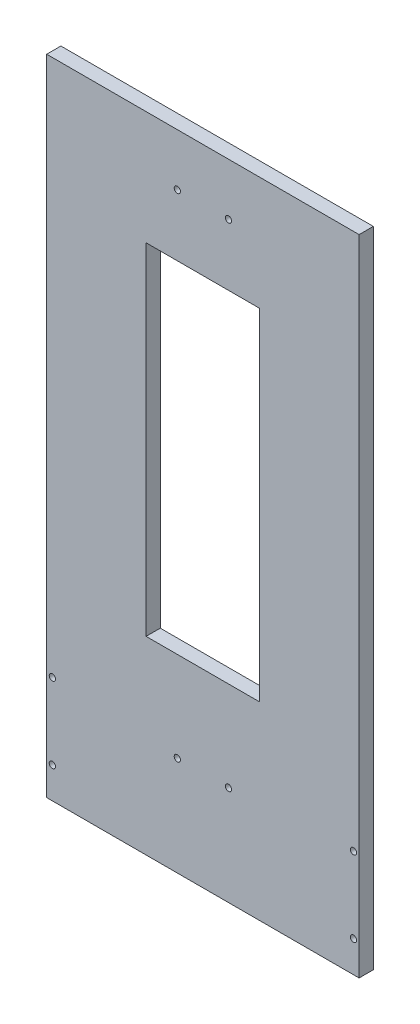
SolidWorks part; units mm, degrees
material "6061 合金"
ref_plane "前视基准面" through (0, 0, 0) normal (0, 0, 1) x (1, 0, 0)
ref_plane "上视基准面" through (0, 0, 0) normal (0, 1, 0) x (1, 0, 0)
ref_plane "右视基准面" through (0, 0, 0) normal (1, 0, 0) x (0, 0, -1)
other "Configuration Table"
sketch "Sketch1" plane through (0, 0, 0) normal (0, 0, 1) x (1, 0, 0)
  line L1 (-165, 0) -> (165, 0)
  line L2 (-165, 0) -> (-165, 680)
  line L3 (-165, 680) -> (165, 680)
  line L4 (165, 0) -> (165, 680)
extrude "Boss-Extrude1" add sketch "Sketch1" along normal blind 15
sketch "Sketch2" plane through (0, 0, 0) normal (0, 0, 1) x (1, 0, 0)
  circle A0 centre (-27, 105) radius 3.3
  circle A1 centre (-27, 625) radius 3.3
  circle A2 centre (27, 105) radius 3.3
  circle A3 centre (27, 625) radius 3.3
extrude "Cut-Extrude1" cut sketch "Sketch2" against normal through all and the other way through all
sketch "Sketch3" plane through (0, 0, 0) normal (0, 0, 1) x (1, 0, 0)
  circle A0 centre (-27, 105) radius 5.5
  circle A1 centre (-27, 625) radius 5.5
  circle A2 centre (27, 105) radius 5.5
  circle A3 centre (27, 625) radius 5.5
extrude "Cut-Extrude3" cut sketch "Sketch3" along normal blind 6.5
sketch "Sketch4" plane through (0, 0, 0) normal (0, 0, 1) x (1, 0, 0)
  circle A0 centre (-159, 33) radius 3.3
  circle A1 centre (-159, 113) radius 3.3
  circle A2 centre (159, 33) radius 3.3
  circle A3 centre (159, 113) radius 3.3
extrude "Cut-Extrude4" cut sketch "Sketch4" against normal through all and the other way through all
sketch "Sketch5" plane through (0, 0, 0) normal (0, 0, 1) x (1, 0, 0)
  circle A0 centre (-159, 33) radius 5.5
  circle A1 centre (-159, 113) radius 5.5
  circle A2 centre (159, 33) radius 5.5
  circle A3 centre (159, 113) radius 5.5
extrude "Cut-Extrude6" cut sketch "Sketch5" along normal blind 6.5
sketch "Sketch6" plane through (0, 0, 0) normal (0, 1, 0) x (1, 0, 0)
  circle A0 centre (-120, -7.5) radius 2.5
  circle A1 centre (-60, -7.5) radius 2.5
  circle A2 centre (60, -7.5) radius 2.5
  circle A3 centre (120, -7.5) radius 2.5
extrude "Cut-Extrude8" cut sketch "Sketch6" along normal blind 15
sketch "Sketch7" plane through (0, 0, 0) normal (0, 0, 1) x (1, 0, 0)
  line L1 (-60, 200) -> (60, 200)
  line L2 (-60, 200) -> (-60, 560)
  line L3 (-60, 560) -> (60, 560)
  line L4 (60, 200) -> (60, 560)
extrude "Cut-Extrude9" cut sketch "Sketch7" against normal through all and the other way through all
